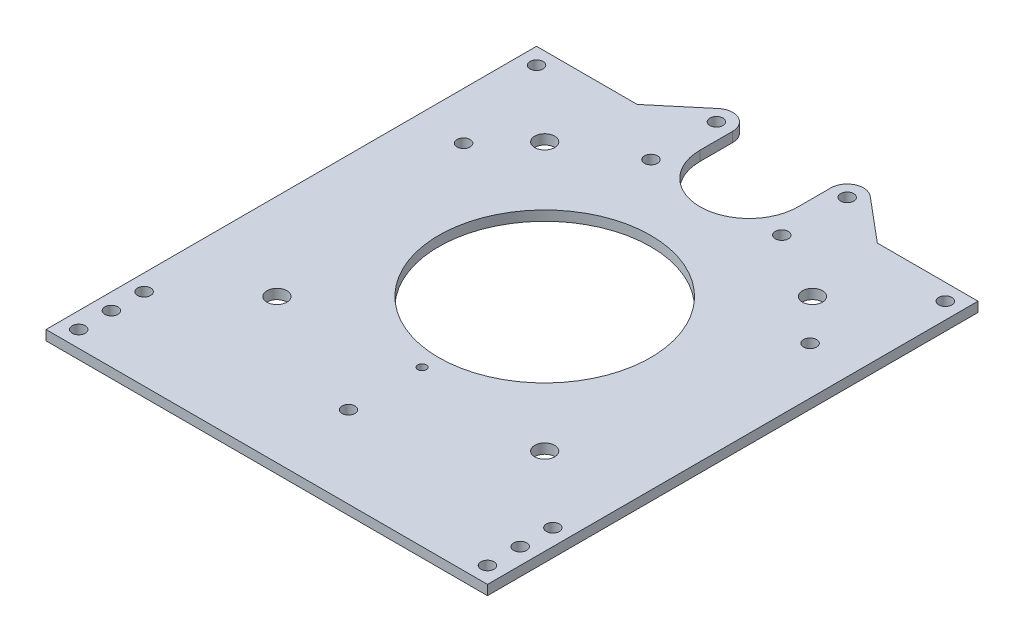
SolidWorks part; units mm, degrees
material "5052-H34"
ref_plane "正面" through (0, 0, 0) normal (0, 0, 1) x (1, 0, 0)
ref_plane "平面" through (0, 0, 0) normal (0, 1, 0) x (1, 0, 0)
ref_plane "右側面" through (0, 0, 0) normal (1, 0, 0) x (0, 0, -1)
sketch "ｽｹｯﾁ1" plane through (0, 0, 0) normal (0, 1, 0) x (1, 0, 0)
  line L0 (67.5, 0) -> (67.5, 85) construction
  line L1 (0, 0) -> (135, 0)
  line L2 (0, 0) -> (0, 150)
  line L3 (0, 150) -> (30.7832, 150)
  line L4 (135, 0) -> (135, 150)
  line L5 (108.4415, 44.0585) -> (67.5, 85) construction
  line L6 (67.5, 85) -> (67.5, 25) construction
  line L7 (67.5, 85) -> (14.5231, 113.1683) construction
  line L8 (67.5, 85) -> (67.5, 147.5) construction
  line L9 (67.5, 147.5) -> (87.5, 147.5) construction
  line L10 (47.5, 157.5) -> (87.5, 157.5) construction
  line L11 (47.5, 157.5) -> (47.5, 137.5) construction
  line L12 (47.5, 137.5) -> (87.5, 137.5) construction
  line L13 (87.5, 157.5) -> (87.5, 137.5) construction
  line L14 (47.5, 157.5) -> (87.5, 137.5) construction
  line L15 (47.5, 137.5) -> (87.5, 157.5) construction
  line L16 (67.5, 85) -> (135, 85) construction
  line L17 (82.5, 157.5) -> (82.5, 150)
  line L18 (52.5, 157.5) -> (52.5, 150)
  line L19 (90.7139, 161.3302) -> (104.2168, 150)
  line L20 (44.2861, 161.3302) -> (30.7832, 150)
  line L21 (30.7832, 150) -> (47.5, 150) construction
  line L22 (47.5, 150) -> (52.7098, 150)
  line L23 (52.5, 157.5) -> (52.5, 147.5)
  line L24 (82.5, 157.5) -> (82.5, 147.5)
  line L25 (79.7474, 150) -> (62.5, 150) construction
  line L26 (82.2902, 150) -> (135, 150)
  line L27 (52.7098, 150) -> (79.7474, 150) construction
  line L28 (62.5, 150) -> (72.5, 150) construction
  line L29 (72.5, 150) -> (79.7474, 150) construction
  line L30 (79.7474, 150) -> (82.2902, 150) construction
  line L31 (135, 75) -> (67.5, 75) construction
  line L32 (130, 5) -> (130, 15) construction
  line L33 (130, 15) -> (130, 25) construction
  circle A0 centre (67.5, 85) radius 32.4
  circle A1 centre (67.5, 85) radius 47.5 construction
  circle A2 centre (108.4415, 44.0585) radius 10.5 construction
  circle A3 centre (108.4415, 44.0585) radius 3.05
  circle A4 centre (26.5585, 44.0585) radius 3.05
  circle A5 centre (26.5585, 44.0585) radius 10.5 construction
  circle A6 centre (26.5585, 125.9415) radius 3.05
  circle A7 centre (26.5585, 125.9415) radius 10.5 construction
  circle A8 centre (108.4415, 125.9415) radius 3.05
  circle A9 centre (108.4415, 125.9415) radius 10.5 construction
  circle A10 centre (67.5, 85) radius 60 construction
  circle A13 centre (67.5, 25) radius 2
  circle A16 centre (14.5231, 113.1683) radius 2
  circle A17 centre (120.4769, 113.1683) radius 2
  circle A18 centre (26.5585, 125.9415) radius 12 construction
  circle A19 centre (14.5231, 113.1683) radius 4 construction
  circle A20 centre (67.5, 47.5) radius 1.3
  circle A21 centre (67.5, 147.5) radius 12.5 construction
  arc A22 (52.7098, 150) -> (82.2902, 150) centre (67.5, 147.5) ccw
  circle A23 centre (67.5, 147.5) radius 21 construction
  circle A24 centre (87.5, 157.5) radius 2
  circle A25 centre (87.5, 137.5) radius 2
  circle A26 centre (47.5, 137.5) radius 2
  circle A27 centre (47.5, 157.5) radius 2
  circle A28 centre (130, 145) radius 2
  circle A30 centre (5, 145) radius 2
  circle A32 centre (87.5, 157.5) radius 5
  circle A33 centre (47.5, 157.5) radius 5
  arc A34 (78.6803, 157.5) -> (56.3197, 157.5) centre (67.5, 147.5) ccw construction
  arc A35 (56.3197, 157.5) -> (54.0836, 154.2082) centre (67.5, 147.5) ccw construction
  arc A36 (54.0836, 154.2082) -> (52.7098, 150) centre (67.5, 147.5) ccw construction
  arc A37 (80.9164, 154.2082) -> (78.6803, 157.5) centre (67.5, 147.5) ccw construction
  arc A38 (82.2902, 150) -> (80.9164, 154.2082) centre (67.5, 147.5) ccw construction
  circle A39 centre (5, 5) radius 2
  circle A40 centre (130, 5) radius 2
  circle A41 centre (130, 15) radius 2
  circle A42 centre (5, 15) radius 2
  circle A43 centre (130, 25) radius 2
  circle A44 centre (5, 25) radius 2
  point P23 (67.5, 85)
  point P31 (67.5, 85)
  point P33 (67.5, 85)
  dimension "D3" = 64.8
  dimension "D5" = 95
  dimension "D6" = 21
  dimension "D7" = 6.1
  dimension "D11" = 120
  dimension "D12" = 4
  dimension "D16" = 24
  dimension "D17" = 8
  dimension "D18" = 25
  dimension "D22" = 42
  dimension "D24" = 4
  dimension "D25" = 4
  dimension "D28" = 2.6
  dimension "D29" = 10
  dimension "D20" = 30
  dimension "D1" = 135
  dimension "D2" = 150
  dimension "D8" = 45
  dimension "D10" = 57.9
  dimension "D14" = 118
  dimension "D4" = 85
  dimension "D15" = 37.5
  dimension "D19" = 62.5
  dimension "D21" = 40
  dimension "D23" = 20
  dimension "D26" = 5
  dimension "D27" = 5
  dimension "D30" = 40
  dimension "D31" = 10
  dimension "D33" = 10
  dimension "D32" = 2
  dimension "D9" = 4
  dimension "D13" = 2
extrude "ﾎﾞｽ - 押し出し1" add sketch "ｽｹｯﾁ1" along normal blind 3
equation "\"D10@ｽｹｯﾁ1\"=\"D5@ｽｹｯﾁ1\"/2+\"D6@ｽｹｯﾁ1\"/2-0.1"
equation "\"D19@ｽｹｯﾁ1\"=\"D18@ｽｹｯﾁ1\"/2+100/2"
